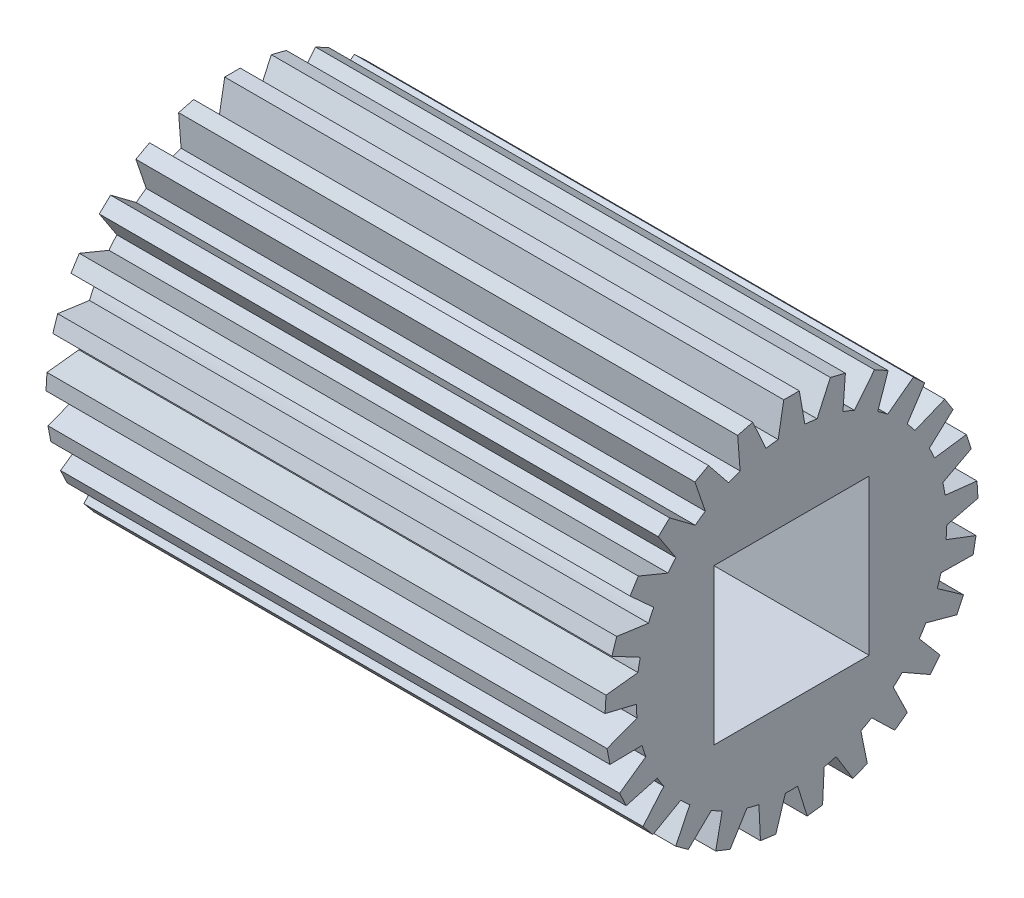
SolidWorks part; units mm, degrees
ref_plane "Front Plane" through (0, 0, 0) normal (0, 0, 1) x (1, 0, 0)
ref_plane "Top Plane" through (0, 0, 0) normal (0, 1, 0) x (1, 0, 0)
ref_plane "Right Plane" through (0, 0, 0) normal (1, 0, 0) x (0, 0, -1)
sketch "Sketch2" plane through (0, 0, 0) normal (1, 0, 0) x (0, 0, -1)
  line L0 (0, 5) -> (0, 6) construction
  line L1 (-0.25, 6) -> (0.25, 6)
  line L2 (-0.25, 6) -> (-0.7008, 3.4435)
  line L3 (-0.7008, 3.4435) -> (0.7008, 3.4435)
  line L4 (0.7008, 3.4435) -> (0.25, 6)
  line L5 (0, 5) -> (0, 3.4435) construction
  arc A0 (0.4296, 4.9815) -> (-0.4296, 4.9815) centre (0, 0) ccw
  point P8 (0, 6)
  dimension "D1" = 10
  dimension "D2" = 1
  dimension "D3" = 0.5
  dimension "D4" = 100
extrude "Boss-Extrude2" add sketch "Sketch2" along normal blind 5 and the other way blind 13 contours L4 A0 L2 L3 | A0 L4 L1 L2
sketch "Sketch3" plane through (0, 0, 0) normal (1, 0, 0) x (0, 0, -1)
  circle A0 centre (0, 0) radius 5
  dimension "D1" = 10
extrude "Boss-Extrude3" add sketch "Sketch3" along normal blind 5 and the other way blind 13
pattern_circular "CirPattern1" count 25 over 360 about axis through (0, 0, 0) along (1, 0, 0) of "Boss-Extrude2"
sketch "Sketch4" plane through (5, 0, 0) normal (1, 0, 0) x (0, 0, -1)
  line L1 (-2.5, -2.5) -> (2.5, -2.5)
  line L2 (-2.5, -2.5) -> (-2.5, 2.5)
  line L3 (-2.5, 2.5) -> (2.5, 2.5)
  line L4 (2.5, -2.5) -> (2.5, 2.5)
  dimension "D1" = 2.5
  dimension "D2" = 5
  dimension "D3" = 5
  dimension "D4" = 2.5
extrude "Cut-Extrude1" cut sketch "Sketch4" against normal blind 18
sketch "Sketch5" plane through (5, 0, 0) normal (1, 0, 0) x (0, 0, -1)
  line L1 (0, -5) -> (0, -6.0359) construction
  circle A0 centre (0, 0) radius 5.5
  arc A1 (-0.1981, -4.9961) -> (0.1981, -4.9961) centre (0, 0) ccw construction
  dimension "D1" = 11
